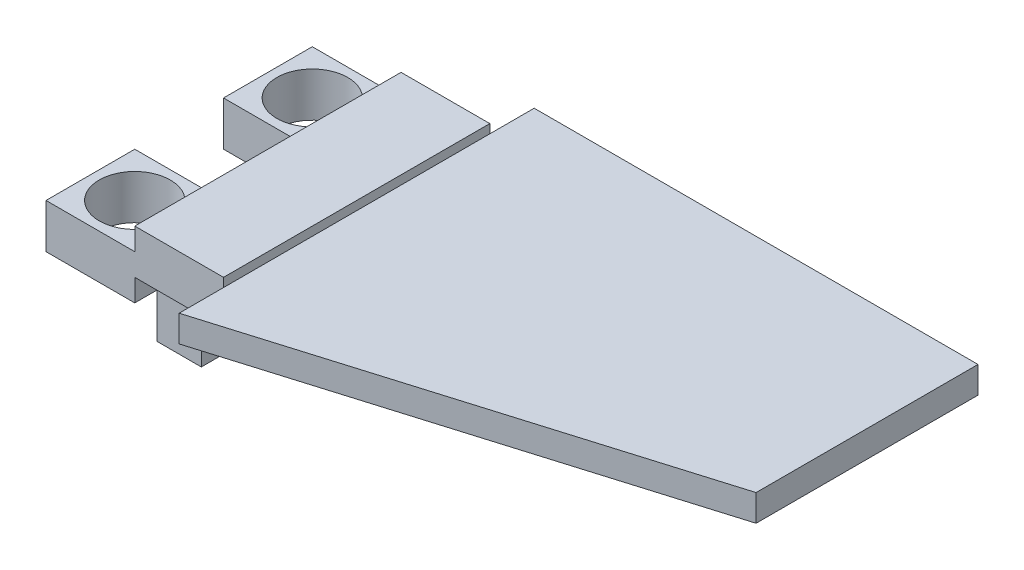
SolidWorks part; units mm, degrees
ref_plane "Front Plane" through (0, 0, 0) normal (0, 0, 1) x (1, 0, 0)
ref_plane "Top Plane" through (0, 0, 0) normal (0, 1, 0) x (1, 0, 0)
ref_plane "Right Plane" through (0, 0, 0) normal (1, 0, 0) x (0, 0, -1)
sketch "Sketch1" plane through (0, 0, 0) normal (0, 1, 0) x (1, 0, 0)
  line L0 (0, 5) -> (10, -5) construction
  line L5 (0, 5) -> (10, 5)
  line L6 (0, 5) -> (0, -5)
  line L7 (0, -5) -> (10, -5)
  line L8 (10, 5) -> (10, -5)
  line L9 (0, -5) -> (10, 5) construction
  line L10 (-2.6397, 10) -> (16.4497, 10) construction
  line L11 (0, 25) -> (10, 15) construction
  line L12 (0, 15) -> (10, 25) construction
  line L13 (10, 15) -> (10, 25)
  line L14 (0, 25) -> (10, 25)
  line L15 (0, 15) -> (0, 25)
  line L16 (0, 15) -> (10, 15)
  circle A0 centre (5, 0) radius 4
  circle A1 centre (5, 20) radius 4
  point P0 (0, 0)
  dimension "D2" = 5
  dimension "D1" = 10
extrude "Boss-Extrude1" add sketch "Sketch1" along normal blind 5
sketch "Sketch2" plane through (10, 0, 0) normal (1, 0, 0) x (0, 0, -1)
  line L0 (-5, 5) -> (5, 5) construction
  line L1 (-2.5, -5) -> (2.5, -5)
  line L2 (-2.5, -5) -> (-2.5, 5)
  line L3 (-2.5, 5) -> (2.5, 5)
  line L4 (2.5, -5) -> (2.5, 5)
  line L5 (-2.5, -5) -> (2.5, 5) construction
  line L6 (-2.5, 5) -> (2.5, -5) construction
  line L7 (15, 0) -> (25, 0) construction
  line L8 (15, 5) -> (25, 5) construction
  line L9 (17.5, -5) -> (22.5, -5)
  line L10 (17.5, -5) -> (17.5, 5)
  line L11 (17.5, 5) -> (22.5, 5)
  line L12 (22.5, -5) -> (22.5, 5)
  line L13 (17.5, -5) -> (22.5, 5) construction
  line L14 (17.5, 5) -> (22.5, -5) construction
  point P0 (0, 0)
  point P10 (20, 0)
  dimension "D1" = 5
extrude "Boss-Extrude2" add sketch "Sketch2" along normal blind 5
sketch "Sketch4" plane through (0, 5, 0) normal (0, 1, 0) x (1, 0, 0)
  line L10 (10, 25) -> (20, 25)
  line L11 (10, 25) -> (10, -5)
  line L12 (10, -5) -> (20, -5)
  line L13 (20, 25) -> (20, -5)
extrude "Boss-Extrude4" add sketch "Sketch4" along normal mid plane 5
sketch "Sketch6" plane through (20, 0, 0) normal (1, 0, 0) x (0, 0, -1)
  line L0 (-18.539, 2.5) -> (43.5819, 2.5)
  line L1 (-5, 2.5) -> (25, 2.5) construction
  line L2 (42.2751, 2.5) -> (44.8886, 2.5) construction
  line L3 (-23.216, 2.5) -> (-13.862, 2.5) construction
  spline S0 degree 3 poles (-18.539, 2.5) (-26.2287, 2.5) (-5.8215, 14.5378) (54.1094, 2.5) (43.5819, 2.5) knots 0 0 0 0 0.416526 1 1 1 1
ref_plane "Plane1" through (0, 5, 0) normal (0, 1, 0) x (1, 0, 0)
sketch "Sketch8" plane through (0, 5, 0) normal (0, 1, 0) x (1, 0, 0)
  line L0 (20, 25) -> (20, 30)
  line L1 (20, 30) -> (70, 30)
  line L2 (70, 30) -> (70, 5)
  line L3 (70, 5) -> (20, -10)
  line L4 (20, -10) -> (20, -5)
  line L9 (10, 25) -> (10, -5)
  line L10 (10, -5) -> (20, -5)
  line L11 (20, -5) -> (20, 25)
  line L12 (20, 25) -> (10, 25)
  line L13 (10, 25) -> (10, -5)
  line L14 (10, -5) -> (20, -5)
  line L16 (20, 25) -> (10, 25)
  dimension "D1" = 5
  dimension "D2" = 5
  dimension "D3" = 25
  dimension "D4" = 0
extrude "Boss-Extrude7" add sketch "Sketch8" along normal mid plane 3 from surface at 0 starting at plane "Plane1"
